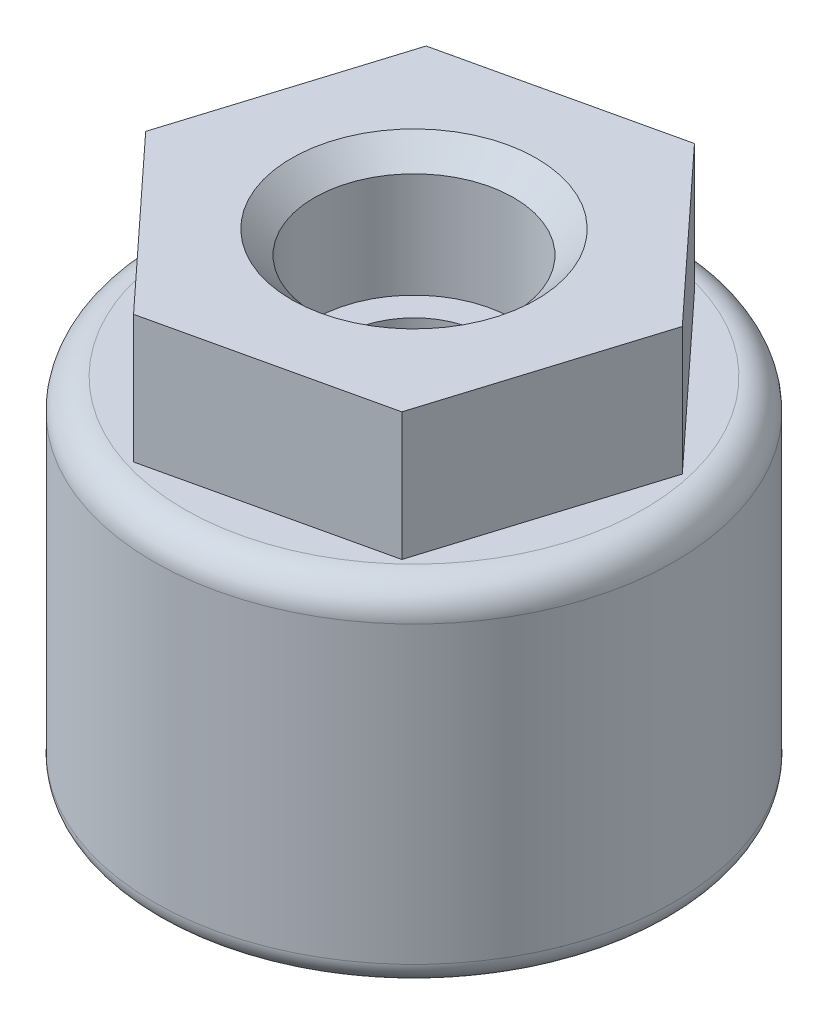
SolidWorks part; units mm, degrees
material "1023 Karbon Çeliği Levha (SS)"
ref_plane "Ön Düzlem" through (0, 0, 0) normal (0, 0, 1) x (1, 0, 0)
ref_plane "Üst Düzlem" through (0, 0, 0) normal (0, 1, 0) x (1, 0, 0)
ref_plane "Sağ Düzlem" through (0, 0, 0) normal (1, 0, 0) x (0, 0, -1)
sketch "Çizim1" plane through (0, 0, 0) normal (0, 1, 0) x (1, 0, 0)
  circle A0 centre (0, 0) radius 14.285
extrude "Yükseklik-Ekstrüzyon1" add sketch "Çizim1" along normal blind 19.1
fillet "Radyus1" radius 1.67 1 edges at (0, 19.1, 14.285)
fillet "Radyus2" radius 1.25 1 edges at (0, 0, 14.285)
sketch "Çizim2" plane through (0, 19.1, 0) normal (0, 1, 0) x (1, 0, 0)
  line L1 (8.3643, -9.0306) -> (12.0029, 2.7284)
  line L2 (12.0029, 2.7284) -> (3.6386, 11.759)
  line L3 (3.6386, 11.759) -> (-8.3643, 9.0306)
  line L4 (-8.3643, 9.0306) -> (-12.0029, -2.7284)
  line L5 (-12.0029, -2.7284) -> (-3.6386, -11.759)
  line L6 (-3.6386, -11.759) -> (8.3643, -9.0306)
  circle A0 centre (0, 0) radius 10.66 construction
extrude "Yükseklik-Ekstrüzyon3" add sketch "Çizim2" along normal blind 7.02
sketch "Çizim4" plane through (0, 26.12, 0) normal (0, 1, 0) x (1, 0, 0)
  circle A0 centre (0, 0) radius 3.95
extrude "Kes-Ekstrüzyon1" cut sketch "Çizim4" against normal blind 29.02 and the other way blind 2
sketch "Çizim5" plane through (0, 26.12, 0) normal (0, 1, 0) x (1, 0, 0)
  circle A0 centre (0, 0) radius 5.475
extrude "Kes-Ekstrüzyon2" cut sketch "Çizim5" against normal blind 7.02
chamfer "Pah1" distance 1.25 angle 45 1 edges at (0, 26.12, 5.475)
